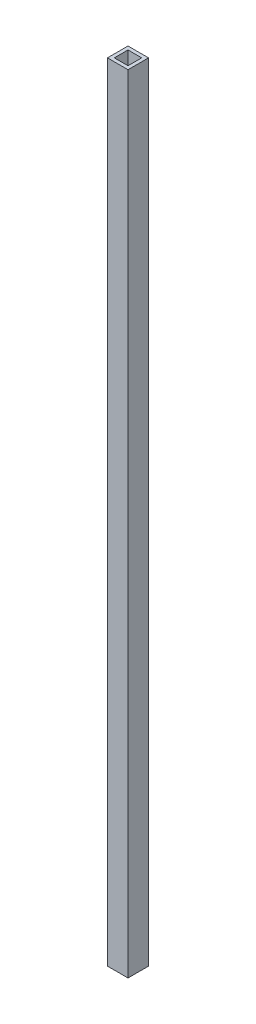
SolidWorks part; units mm, degrees
ref_plane "Front Plane" through (0, 0, 0) normal (0, 0, 1) x (1, 0, 0)
ref_plane "Top Plane" through (0, 0, 0) normal (0, 1, 0) x (1, 0, 0)
ref_plane "Right Plane" through (0, 0, 0) normal (1, 0, 0) x (0, 0, -1)
sketch "Sketch1" plane through (0, 0, 0) normal (0, 1, 0) x (1, 0, 0)
  line L1 (0, 0) -> (19.05, 0)
  line L2 (0, 0) -> (0, 19.05)
  line L3 (0, 19.05) -> (19.05, 19.05)
  line L4 (19.05, 0) -> (19.05, 19.05)
  dimension "D1" = 19.05
  dimension "D2" = 19.05
extrude "Extrude-Thin1" add sketch "Sketch1" along normal blind 730.25 thin thin type one direction reverse wall 3.175
